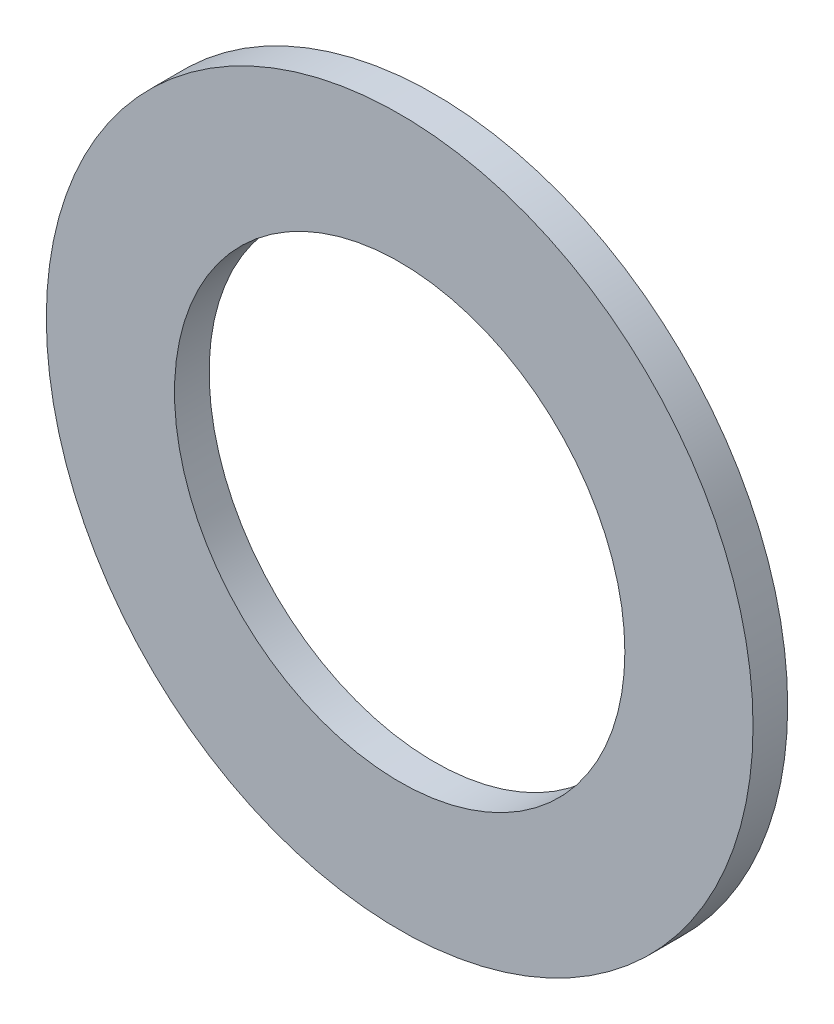
SolidWorks part; units mm, degrees
material "Pure Gold"
ref_plane "Front" through (0, 0, 0) normal (0, 0, 1) x (1, 0, 0)
ref_plane "Top" through (0, 0, 0) normal (0, 1, 0) x (1, 0, 0)
ref_plane "Right" through (0, 0, 0) normal (1, 0, 0) x (0, 0, -1)
sketch "Sketch1" plane through (0, 0, 0) normal (0, 0, 1) x (1, 0, 0)
  line L0 (-5.1, 0) -> (5.1, 0) construction
  line L7 (0, -5.1) -> (0, 5.1) construction
  circle A3 centre (0, 0) radius 3.25
  circle A6 centre (0, 0) radius 5.1
  point P2 (5.5, 0)
  point P3 (0, -5.5)
  point P11 (0, 0)
  point P14 (0, 0)
  dimension "D4" = 6.5
  dimension "D7" = 10.2
extrude "Boss-Extrude1" add sketch "Sketch1" along normal blind 0.5
